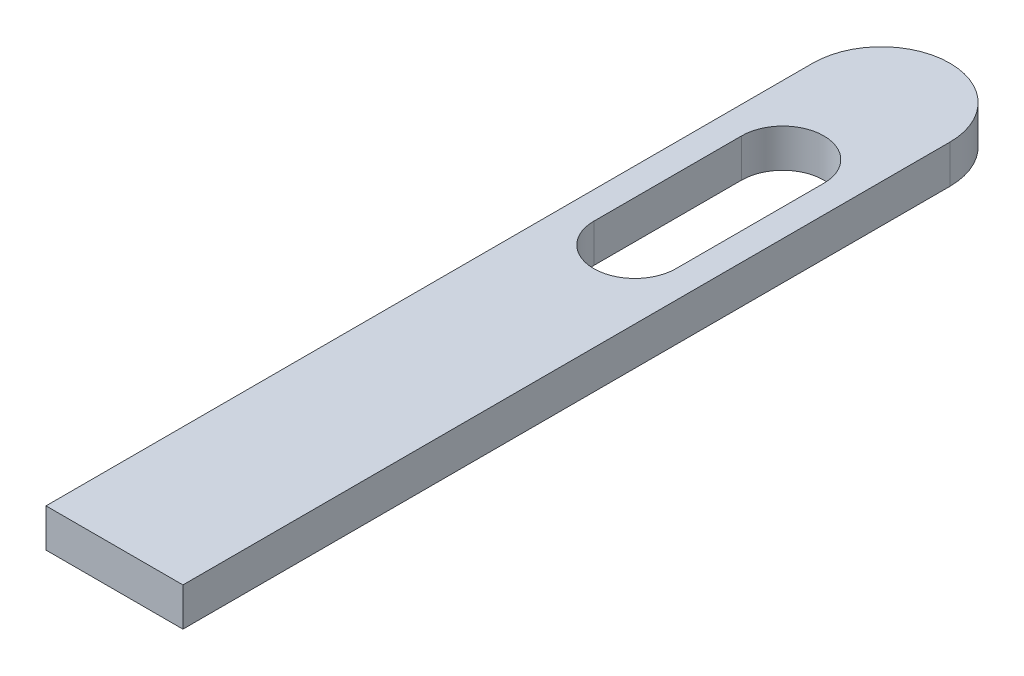
SolidWorks part; units mm, degrees
material "AISI 316 Stainless Steel Sheet (SS)"
ref_plane "Front Plane" through (0, 0, 0) normal (0, 0, 1) x (1, 0, 0)
ref_plane "Top Plane" through (0, 0, 0) normal (0, 1, 0) x (1, 0, 0)
ref_plane "Right Plane" through (0, 0, 0) normal (1, 0, 0) x (0, 0, -1)
sketch "Sketch1" plane through (0, 0, 0) normal (0, 1, 0) x (1, 0, 0)
  line L0 (0, 2.6) -> (0, 1.25) construction
  line L1 (-0.625, 3.5) -> (0.625, 3.5) construction
  line L2 (-0.625, 3.5) -> (-0.625, -3.5)
  line L3 (-0.625, -3.5) -> (0.625, -3.5)
  line L4 (0.625, 3.5) -> (0.625, -3.5)
  line L5 (-0.625, 3.5) -> (0.625, -3.5) construction
  line L6 (-0.625, -3.5) -> (0.625, 3.5) construction
  line L7 (0.375, 2.6) -> (0.375, 1.25)
  line L8 (-0.375, 2.6) -> (-0.375, 1.25)
  line L9 (0, 2.975) -> (0.6302, 2.975) construction
  line L10 (0, 4.125) -> (0.9704, 4.125) construction
  arc A0 (-0.625, 3.5) -> (0.625, 3.5) centre (0, 3.5) cw
  arc A1 (0.375, 2.6) -> (-0.375, 2.6) centre (0, 2.6) ccw
  arc A2 (-0.375, 1.25) -> (0.375, 1.25) centre (0, 1.25) ccw
  point P0 (0, 0)
  point P6 (0, 1.925)
  dimension "D3" = 1.35
  dimension "D1" = 7
  dimension "D2" = 1.25
  dimension "D4" = 0.75
  dimension "D5" = 1.15
extrude "Boss-Extrude2" add sketch "Sketch1" along normal mid plane 0.35
